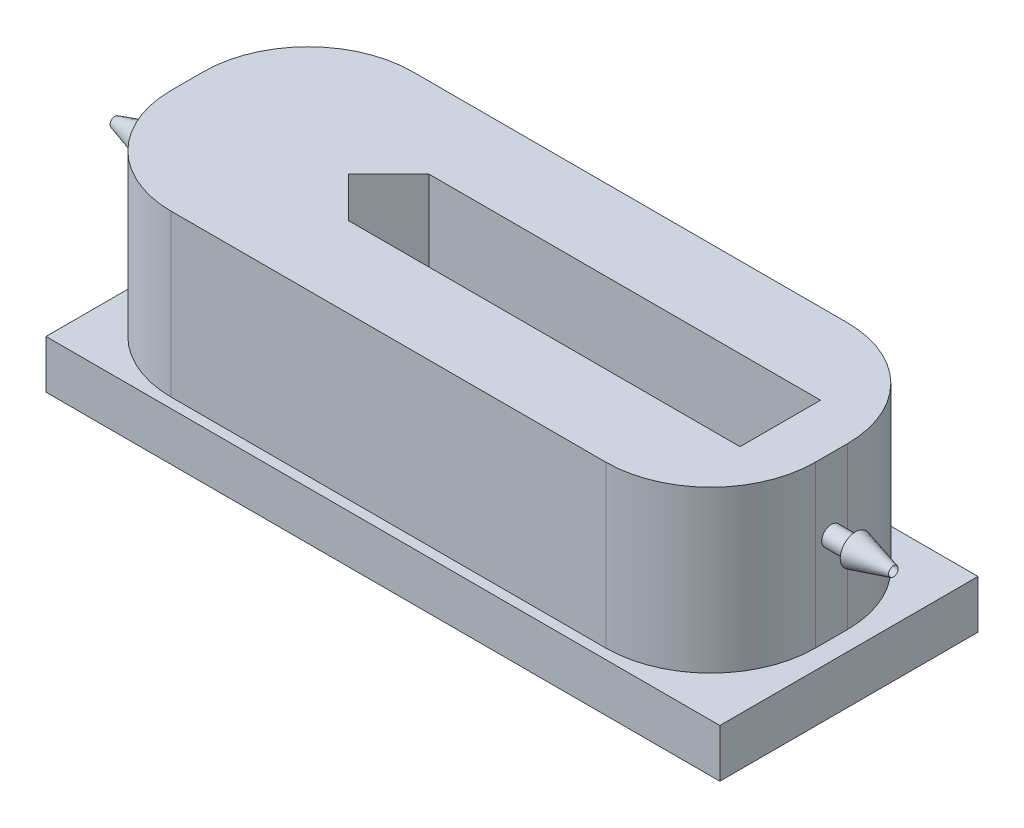
SolidWorks part; units mm, degrees
ref_plane "Front Plane" through (0, 0, 0) normal (0, 0, 1) x (1, 0, 0)
ref_plane "Top Plane" through (0, 0, 0) normal (0, 1, 0) x (1, 0, 0)
ref_plane "Right Plane" through (0, 0, 0) normal (1, 0, 0) x (0, 0, -1)
sketch "Sketch1" plane through (0, 0, 0) normal (0, 1, 0) x (1, 0, 0)
  line L1 (-40, -15) -> (40, -15)
  line L2 (-40, -15) -> (-40, 15)
  line L3 (-40, 15) -> (40, 15)
  line L4 (40, -15) -> (40, 15)
  line L5 (-40, -15) -> (40, 15) construction
  line L6 (-40, 15) -> (40, -15) construction
  point P0 (0, 0)
  dimension "D1" = 30
  dimension "D2" = 80
extrude "Boss-Extrude1" add sketch "Sketch1" along normal blind 60
sketch "Sketch2" plane through (0, 60, 0) normal (0, 1, 0) x (1, 0, 0)
  line L0 (-15, 5) -> (15, 5)
  line L3 (15, -5) -> (-15, -5)
  line L4 (-15, -5) -> (-20, 0)
  line L5 (-20, 0) -> (-15, 5)
  line L6 (15, 5) -> (33.657, 5)
  line L7 (33.657, 5) -> (33.657, -5)
  line L8 (33.657, -5) -> (15, -5)
  dimension "D1" = 15
  dimension "D2" = 15
  dimension "D3" = 15
  dimension "D4" = 15
  dimension "D5" = 5
  dimension "D6" = 5
extrude "Cut-Extrude1" cut sketch "Sketch2" against normal blind 75
sketch "Sketch3" plane through (-40, 0, 0) normal (-1, 0, 0) x (0, 0, 1)
  circle A0 centre (0, 51.112) radius 0.8
  dimension "D1" = 1.6
extrude "Cut-Extrude2" cut sketch "Sketch3" against normal through all and the other way through all
sketch "Sketch4" plane through (-40, 0, 0) normal (-1, 0, 0) x (0, 0, 1)
  circle A0 centre (0, 51.112) radius 1.5
  circle A1 centre (0, 51.112) radius 1.2
  dimension "D1" = 2.4
  dimension "D2" = 3
extrude "Boss-Extrude2" add sketch "Sketch4" along normal blind 3
sketch "Sketch6" plane through (0, 0, 0) normal (0, 0, 1) x (1, 0, 0)
  line L0 (-43, 51.112) -> (-49.3252, 51.112)
  line L1 (-43, 52.612) -> (-43, 49.612) construction
  line L2 (-43, 51.112) -> (-43, 53.512)
  line L3 (-43, 53.512) -> (-49.3252, 51.612)
  line L4 (-49.3252, 51.612) -> (-49.3252, 51.112)
  dimension "D1" = 2.4
  dimension "D2" = 0.5
revolve "Revolve1" add sketch "Sketch6" angle 360 about L0
sketch "Sketch7" plane through (-49.3252, 0, 0) normal (-1, 0, 0) x (0, 0, 1)
  circle A0 centre (0, 51.112) radius 0.6
  dimension "D1" = 1.2
extrude "Cut-Extrude3" cut sketch "Sketch7" against normal blind 2
sketch "Sketch8" plane through (-47.3252, 0, 0) normal (-1, 0, 0) x (0, 0, 1)
  circle A0 centre (0, 51.112) radius 0.8
  dimension "D1" = 1.6
extrude "Cut-Extrude4" cut sketch "Sketch8" against normal blind 53
fillet "Fillet1" radius 13 4 edges at (40, 30, -15) (-40, 30, -15) (40, 30, 15) (-40, 30, 15)
sketch "Sketch9" plane through (40, 0, 0) normal (1, 0, 0) x (0, 0, -1)
  circle A0 centre (0, 51.112) radius 0.8
  circle A1 centre (0, 51.112) radius 1.2
  dimension "D1" = 2.4
extrude "Boss-Extrude3" add sketch "Sketch9" along normal blind 3
sketch "Sketch11" plane through (0, 0, 0) normal (0, 0, 1) x (1, 0, 0)
  line L0 (43, 51.112) -> (43, 53.0133)
  line L1 (43, 49.912) -> (43, 52.312) construction
  line L2 (43, 51.112) -> (47.7051, 51.112)
  line L3 (47.7051, 51.112) -> (47.7051, 51.712)
  line L4 (47.7051, 51.712) -> (43, 53.0133)
  dimension "D1" = 0.6
  dimension "D2" = 1.9014
  dimension "D3" = 4.7051
revolve "Revolve2" add sketch "Sketch11" angle 360 about L2
sketch "Sketch12" plane through (47.7051, 0, 0) normal (1, 0, 0) x (0, 0, -1)
  circle A0 centre (0, 51.112) radius 0.6
extrude "Cut-Extrude5" cut sketch "Sketch12" against normal blind 2
sketch "Sketch14" plane through (45.7051, 0, 0) normal (1, 0, 0) x (0, 0, -1)
  circle A0 centre (0, 51.112) radius 0.8
extrude "Cut-Extrude6" cut sketch "Sketch14" against normal blind 35
ref_plane "Plane2" through (0, -10, 0) normal (0, -1, 0) x (-1, 0, 0)
sketch "Sketch15" plane through (0, -10, 0) normal (0, -1, 0) x (-1, 0, 0)
  line L1 (-41.9055, 15.8797) -> (41.7906, 15.8797)
  line L2 (-41.9055, 15.8797) -> (-41.9055, -15.8187)
  line L3 (-41.9055, -15.8187) -> (41.7906, -15.8187)
  line L4 (41.7906, 15.8797) -> (41.7906, -15.8187)
extrude "Cut-Extrude7" cut sketch "Sketch15" against normal blind 50
ref_plane "Plane3" through (0, 40, 0) normal (0, -1, 0) x (-1, 0, 0)
sketch "Sketch16" plane through (0, 40, 0) normal (0, -1, 0) x (-1, 0, 0)
  line L1 (-42.3932, 15.8187) -> (41.3029, 15.8187)
  line L2 (-42.3932, 15.8187) -> (-42.3932, -16.2455)
  line L3 (-42.3932, -16.2455) -> (41.3029, -16.2455)
  line L4 (41.3029, 15.8187) -> (41.3029, -16.2455)
extrude "Boss-Extrude4" add sketch "Sketch16" along normal blind 6
